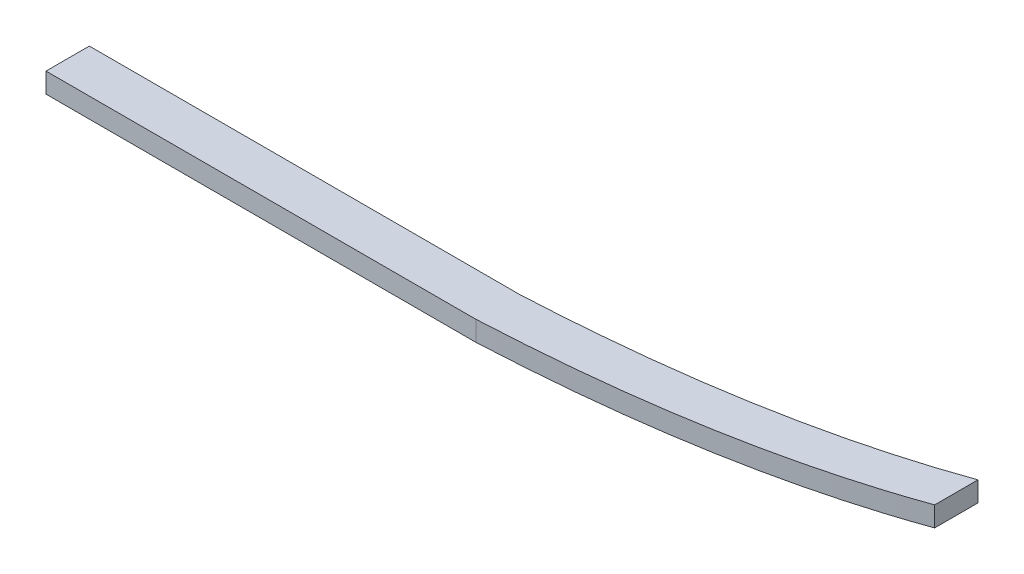
SolidWorks part; units mm, degrees
ref_plane "Front Plane" through (0, 0, 0) normal (0, 0, 1) x (1, 0, 0)
ref_plane "Top Plane" through (0, 0, 0) normal (0, 1, 0) x (1, 0, 0)
ref_plane "Right Plane" through (0, 0, 0) normal (1, 0, 0) x (0, 0, -1)
sketch "Sketch1" plane through (0, 0, 0) normal (0, 1, 0) x (1, 0, 0)
  line L0 (0, 0) -> (120, 0) construction
  line L1 (-55, 0) -> (55, 0) construction
  line L2 (0, 0) -> (61.5, 0)
  line L3 (0, 0) -> (0, 10.3) construction
  line L4 (0, -55) -> (0, 55) construction
  line L5 (0, 10.3) -> (120.0261, 10.3) construction
  line L6 (120.0261, 10.3) -> (120, 0) construction
  line L7 (120, 0) -> (0, 0) construction
  line L9 (0, 6.5) -> (61.5, 6.5)
  line L10 (120.0261, 10.3) -> (120.0288, 16.8032)
  line L11 (0, 6.5) -> (-3, 6.5)
  line L12 (-3, 6.5) -> (-3, 0)
  line L13 (-3, 0) -> (0, 0)
  spline S0 degree 2 poles (61.5, 0) (96.0799, 1.6899) (120.0261, 10.3) knots 0 0 0 1 1 1
  spline S1 degree 2 poles (61.5, 6.5) (96.0825, 8.1932) (120.0288, 16.8032) knots 0 0 0 1 1 1
  dimension "D1" = 120
  dimension "D2" = 61.5
  dimension "D3" = 10.3
  dimension "D4" = 6.5
  dimension "D5" = 3
extrude "Boss-Extrude1" add sketch "Sketch1" along normal blind 3
